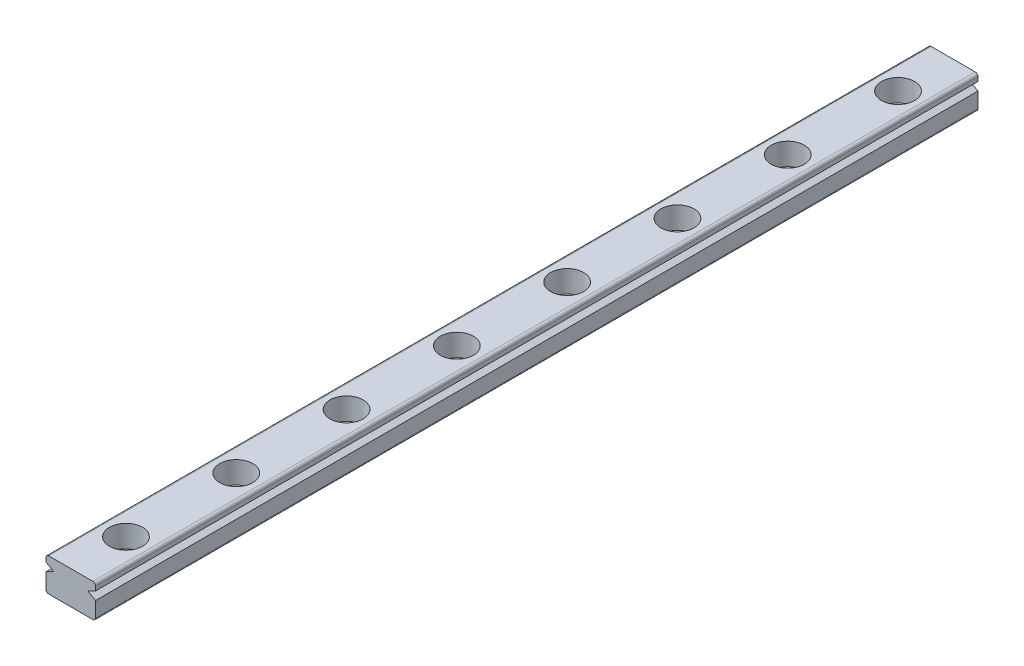
SolidWorks part; units mm, degrees
ref_plane "Front Plane" through (0, 0, 0) normal (0, 0, 1) x (1, 0, 0)
ref_plane "Top Plane" through (0, 0, 0) normal (0, 1, 0) x (1, 0, 0)
ref_plane "Right Plane" through (0, 0, 0) normal (1, 0, 0) x (0, 0, -1)
sketch "Sketch1" plane through (0, 0, 0) normal (0, 0, 1) x (1, 0, 0)
  line L0 (-4.5, 0) -> (4.5, 0)
  line L1 (4.5, 0) -> (4.5, 3.25)
  line L2 (4.5, 3.25) -> (3.1, 4)
  line L3 (3.1, 4) -> (4.5, 4.75)
  line L4 (4.5, 4.75) -> (4.5, 6)
  line L5 (4.5, 6) -> (-4.5, 6)
  line L6 (-4.5, 6) -> (-4.5, 4.75)
  line L7 (-4.5, 4.75) -> (-3.1, 4)
  line L8 (-3.1, 4) -> (-4.5, 3.25)
  line L9 (-4.5, 3.25) -> (-4.5, 0)
  point P3 (0, 0)
  dimension "D1" = 9
  dimension "D2" = 6
  dimension "D3" = 2
  dimension "D4" = 0.75
  dimension "D5" = 0.75
  dimension "D6" = 1.4
extrude "Boss-Extrude1" add sketch "Sketch1" along normal blind 160
fillet "Fillet1" radius 0.5 4 edges at (4.5, 0, 80) (-4.5, 0, 80) (-4.5, 6, 80) (4.5, 6, 80)
sketch "Sketch2" plane through (0, 6, 0) normal (0, 1, 0) x (1, 0, 0)
  line L0 (4, 0) -> (-4, 0) construction
  circle A0 centre (0, -10) radius 3
  point P5 (0, 0)
  dimension "D2" = 6
  dimension "D1" = 10
extrude "Cut-Extrude1" cut sketch "Sketch2" against normal blind 4
sketch "Sketch3" plane through (0, 2, 0) normal (0, 1, 0) x (1, 0, 0)
  circle A0 centre (0, -10) radius 1.75
extrude "Cut-Extrude2" cut sketch "Sketch3" against normal through all
pattern_linear "LPattern1" count 8 spacing 20 along (0, 0, 1) of "Cut-Extrude1", "Cut-Extrude2"
